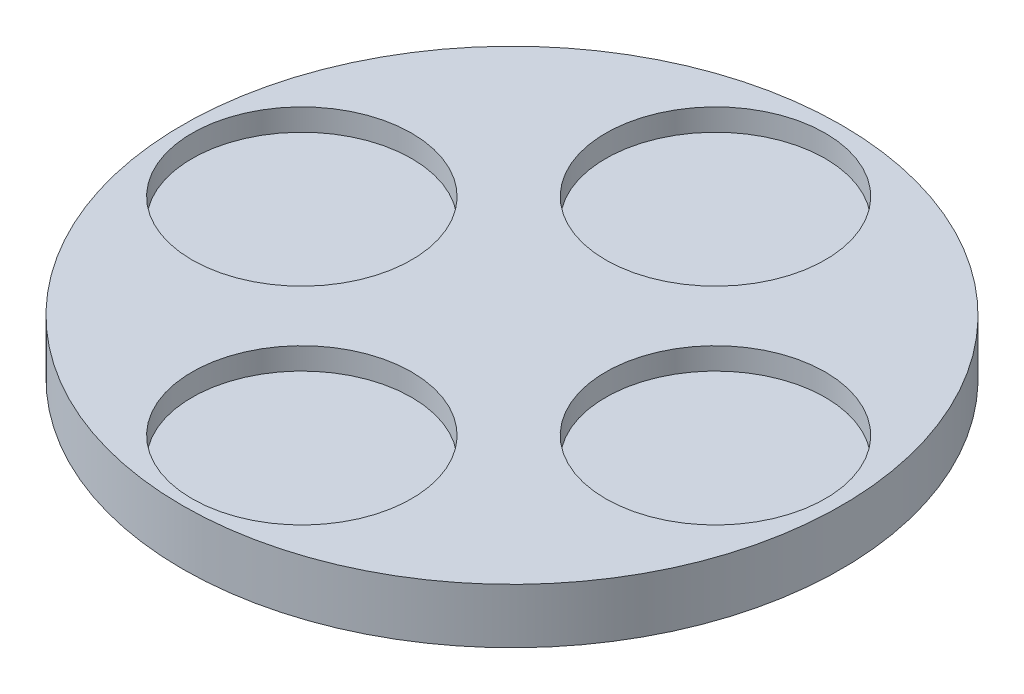
SolidWorks part; units mm, degrees
ref_plane "Front Plane" through (0, 0, 0) normal (0, 0, 1) x (1, 0, 0)
ref_plane "Top Plane" through (0, 0, 0) normal (0, 1, 0) x (1, 0, 0)
ref_plane "Right Plane" through (0, 0, 0) normal (1, 0, 0) x (0, 0, -1)
sketch "Sketch1" plane through (0, 0, 0) normal (0, 1, 0) x (1, 0, 0)
  circle A0 centre (0.2578, 0.5155) radius 76.2273
extrude "Boss-Extrude1" add sketch "Sketch1" along normal blind 12.7 contours A0
sketch "Sketch3" plane through (0, 12.7, 0) normal (0, 1, 0) x (1, 0, 0)
sketch "Sketch5" plane through (0, 12.7, 0) normal (0, 1, 0) x (1, 0, 0)
  circle A0 centre (0, 47.8379) radius 25.4
  circle A1 centre (47.8379, 0) radius 25.4
  circle A2 centre (0, -47.8379) radius 25.4
  circle A3 centre (-47.8379, 0) radius 25.4
  point P8 (0, 0)
  point P9 (0, 47.8379)
  point P11 (0, 0)
  point P12 (46.3668, 0)
  point P13 (0, -46.6047)
  point P14 (-47.0647, 0)
extrude "Cut-Extrude2" cut sketch "Sketch5" against normal blind 5.08 contours A3
sketch "Sketch7" plane through (0, 12.7, 0) normal (0, 1, 0) x (1, 0, 0)
  circle A0 centre (0, 47.8379) radius 25.4
  circle A1 centre (47.8379, 0) radius 25.4
  circle A2 centre (0, -47.8379) radius 25.4
  point P6 (0, 0)
  point P7 (0, 0)
  point P8 (0, 49.1993)
  point P9 (47.768, 0)
  point P10 (0, -44.3878)
extrude "Cut-Extrude4" cut sketch "Sketch7" against normal blind 5.08 contours A0 | A1 | A2
sketch "Sketch8" plane through (0, 12.7, 0) normal (0, 1, 0) x (1, 0, 0)
  line L0 (-22.4379, 0) -> (-75.9695, 0.5155)
  circle A6 centre (-47.8379, 0) radius 25.4 construction
  circle A7 centre (-47.8379, 0) radius 25.4 construction
  circle A8 centre (0.2578, 0.5155) radius 76.2273 construction
